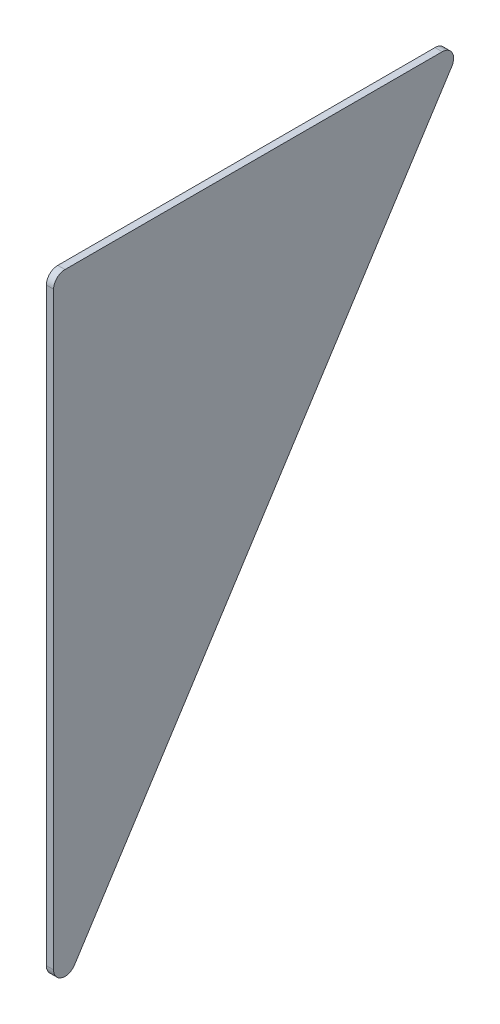
SolidWorks part; units mm, degrees
material "Acrylic (Medium-high impact)"
ref_plane "Front Plane" through (0, 0, 0) normal (0, 0, 1) x (1, 0, 0)
ref_plane "Top Plane" through (0, 0, 0) normal (0, 1, 0) x (1, 0, 0)
ref_plane "Right Plane" through (0, 0, 0) normal (1, 0, 0) x (0, 0, -1)
sketch "Sketch1" plane through (0, 0, 0) normal (1, 0, 0) x (0, 0, -1)
  line L0 (5, 0) -> (170.8635, 0)
  line L1 (0, -5) -> (0, -264.1525)
  line L2 (9.2113, -266.8478) -> (175.0748, -7.6953)
  arc A0 (0, -264.1525) -> (9.2113, -266.8478) centre (5, -264.1525) ccw
  arc A1 (5, 0) -> (0, -5) centre (5, -5) ccw
  arc A2 (170.8635, 0) -> (175.0748, -7.6953) centre (170.8635, -5) cw
  point P6 (0, -281.24)
  point P9 (0, 0)
  point P12 (180, 0)
  dimension "D3" = 5
  dimension "D1" = 180
  dimension "D2" = 281.24
extrude "Boss-Extrude1" add sketch "Sketch1" along normal blind 3.175
